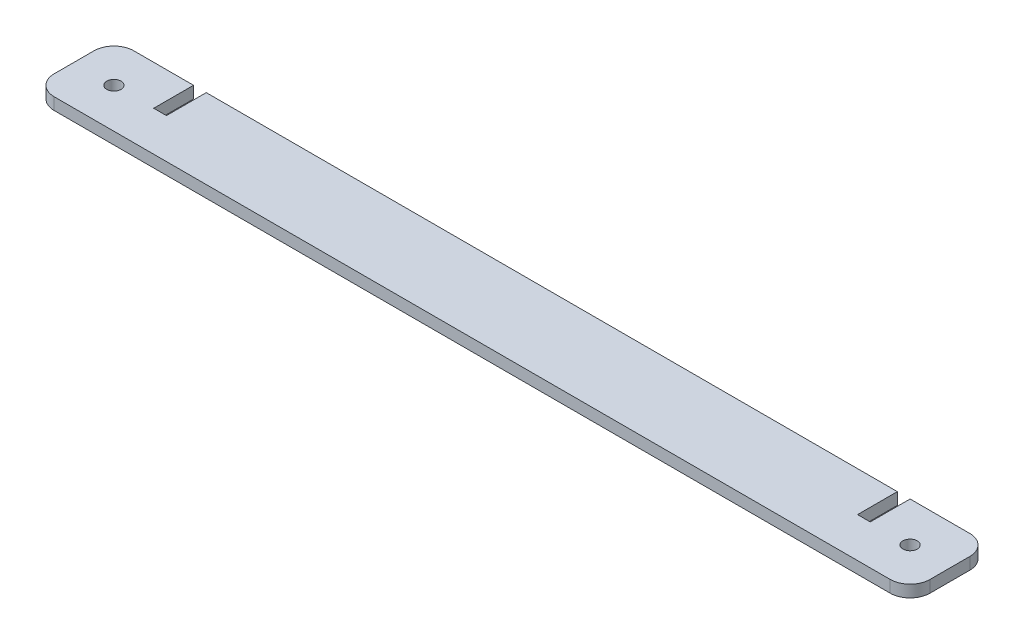
SolidWorks part; units mm, degrees
ref_plane "Front" through (0, 0, 0) normal (0, 0, 1) x (1, 0, 0)
ref_plane "Top" through (0, 0, 0) normal (0, 1, 0) x (1, 0, 0)
ref_plane "Right" through (0, 0, 0) normal (1, 0, 0) x (0, 0, -1)
sketch "草图1" plane through (0, 0, 0) normal (0, 1, 0) x (1, 0, 0)
  line L0 (-90, 10) -> (-90, 0)
  line L1 (-105, 10) -> (-90, 10)
  line L2 (-110, 5) -> (-110, -5)
  line L3 (-105, -10) -> (105, -10)
  line L4 (110, 5) -> (110, -5)
  line L5 (0, -10) -> (0, 10) construction
  line L6 (-110, 0) -> (110, 0) construction
  line L7 (-90, 0) -> (-86.8, 0)
  line L8 (-86.8, 0) -> (-86.8, 10)
  line L9 (-86.8, 10) -> (86.8, 10)
  line L10 (90, 0) -> (86.8, 0)
  line L11 (90, 10) -> (90, 0)
  line L12 (86.8, 0) -> (86.8, 10)
  line L13 (90, 10) -> (105, 10)
  arc A0 (105, 10) -> (110, 5) centre (105, 5) cw
  arc A1 (105, -10) -> (110, -5) centre (105, -5) ccw
  arc A2 (-105, -10) -> (-110, -5) centre (-105, -5) cw
  arc A3 (-110, 5) -> (-105, 10) centre (-105, 5) cw
  circle A4 centre (-100, 0) radius 1.8
  circle A5 centre (100, 0) radius 1.8
  point P0 (0, 0)
  point P6 (110, 10)
  point P12 (110, -10)
  point P17 (-110, 10)
  point P24 (0, 0)
  dimension "D3" = 5
  dimension "D4" = 10
  dimension "D5" = 10
  dimension "D6" = 3.6
  dimension "D7" = 3.6
  dimension "D1" = 220
  dimension "D2" = 20
  dimension "D8" = 3.2
  dimension "D9" = 20
extrude "凸台-拉伸1" add sketch "草图1" along normal blind 3
